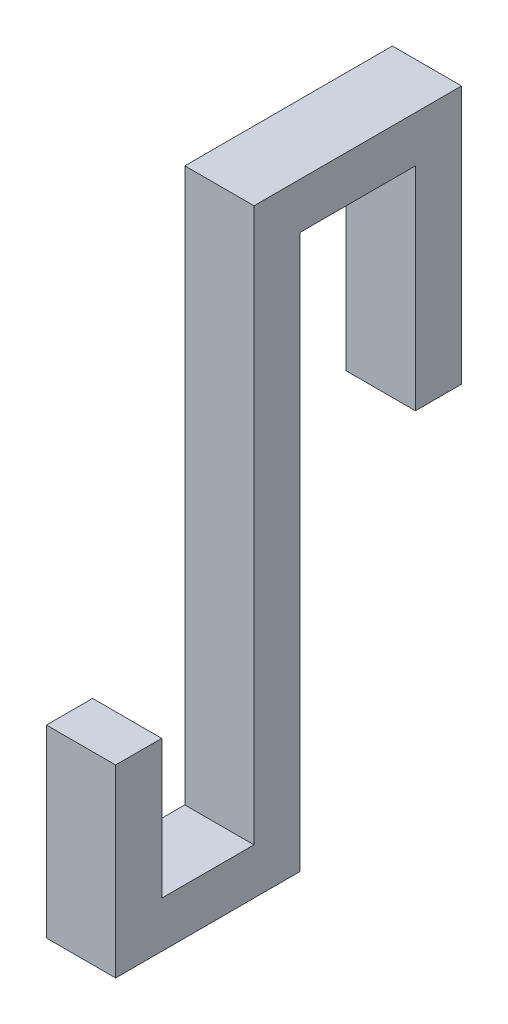
SolidWorks part; units mm, degrees
ref_plane "Front Plane" through (0, 0, 0) normal (0, 0, 1) x (1, 0, 0)
ref_plane "Top Plane" through (0, 0, 0) normal (0, 1, 0) x (1, 0, 0)
ref_plane "Right Plane" through (0, 0, 0) normal (1, 0, 0) x (0, 0, -1)
sketch "Sketch1" plane through (0, 0, 0) normal (1, 0, 0) x (0, 0, -1)
  line L0 (40.8241, 21.0609) -> (40.8241, 77.0609)
  line L1 (40.8241, 77.0609) -> (-4.1759, 77.0609)
  line L2 (-4.1759, 77.0609) -> (-4.1759, -52.9391)
  line L3 (-4.1759, -52.9391) -> (5.8241, -52.9391)
  line L4 (5.8241, -52.9391) -> (5.8241, 67.0609)
  line L5 (5.8241, 67.0609) -> (30.8241, 67.0609)
  line L6 (30.8241, 67.0609) -> (30.8241, 21.0609)
  line L7 (30.8241, 21.0609) -> (40.8241, 21.0609)
  line L8 (-4.1759, -52.9391) -> (-34.1759, -52.9391)
  line L9 (-34.1759, -52.9391) -> (-34.1759, -12.9391)
  line L10 (-34.1759, -12.9391) -> (-24.1759, -12.9391)
  line L11 (-24.1759, -12.9391) -> (-24.1759, -42.9391)
  line L12 (-24.1759, -42.9391) -> (-4.1759, -42.9391)
  dimension "D1" = 10
  dimension "D2" = 10
  dimension "D3" = 25
  dimension "D4" = 120
  dimension "D5" = 46
  dimension "D6" = 10
  dimension "D7" = 10
  dimension "D8" = 20
  dimension "D9" = 10
  dimension "D10" = 30
extrude "Boss-Extrude1" add sketch "Sketch1" along normal blind 15 contours L6 L7 L0 L1 L2 L3 L4 L5 | L12 L11 L10 L9 L8 L2
